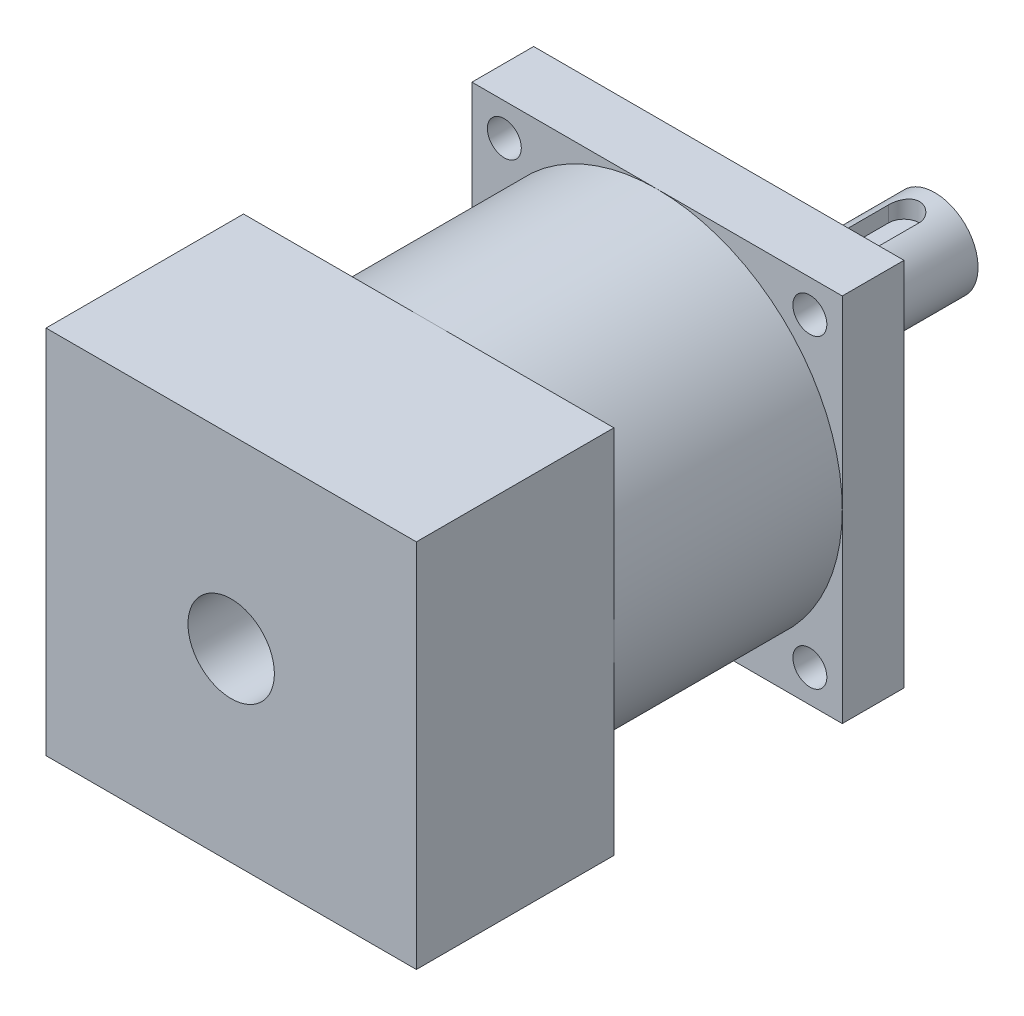
SolidWorks part; units mm, degrees
ref_plane "前视基准面" through (0, 0, 0) normal (0, 0, 1) x (1, 0, 0)
ref_plane "上视基准面" through (0, 0, 0) normal (0, 1, 0) x (1, 0, 0)
ref_plane "右视基准面" through (0, 0, 0) normal (1, 0, 0) x (0, 0, -1)
sketch "草图1" plane through (0, 0, 0) normal (0, 0, 1) x (1, 0, 0)
  line L1 (0, 0) -> (60, 0)
  line L2 (0, 0) -> (0, -60)
  line L3 (0, -60) -> (60, -60)
  line L4 (60, 0) -> (60, -60)
  dimension "D1" = 60
  dimension "D2" = 60
extrude "拉伸1" add sketch "草图1" along normal blind 10
sketch "草图3" plane through (0, 0, 10) normal (0, 0, 1) x (1, 0, 0)
  circle A0 centre (30, -30) radius 30
  dimension "D1" = 60
extrude "拉伸2" add sketch "草图3" along normal blind 37
sketch "草图4" plane through (0, 0, 47) normal (0, 0, 1) x (1, 0, 0)
  line L1 (0, 0) -> (60, 0)
  line L2 (0, 0) -> (0, -60)
  line L3 (0, -60) -> (60, -60)
  line L4 (60, 0) -> (60, -60)
extrude "拉伸3" add sketch "草图4" along normal blind 32
sketch "草图5" plane through (0, 0, 0) normal (0, 0, -1) x (-1, 0, 0)
  circle A0 centre (-30, -30) radius 25
extrude "拉伸4" add sketch "草图5" along normal blind 3
sketch "草图6" plane through (0, 0, -3) normal (0, 0, -1) x (-1, 0, 0)
  circle A0 centre (-30, -30) radius 8.5
extrude "拉伸5" add sketch "草图6" along normal blind 2
sketch "草图7" plane through (0, 0, -5) normal (0, 0, -1) x (-1, 0, 0)
  circle A0 centre (-30, -30) radius 7
extrude "拉伸6" add sketch "草图7" along normal blind 30
sketch "草图8" plane through (0, 0, 79) normal (0, 0, 1) x (1, 0, 0)
  circle A0 centre (30, -30) radius 7
extrude "切除-拉伸1" cut sketch "草图8" against normal blind 30
sketch "草图9" plane through (0, 0, 0) normal (0, 0, -1) x (-1, 0, 0)
  circle A1 centre (-5.2513, -5.2513) radius 2.75
  circle A2 centre (-5.2513, -54.7487) radius 2.75
  circle A3 centre (-54.7487, -54.7487) radius 2.75
  circle A4 centre (-54.7487, -5.2513) radius 2.75
extrude "切除-拉伸2" cut sketch "草图9" against normal blind 30
ref_plane "基准面2" through (0, -23, 0) normal (0, 1, 0) x (-1, 0, 0)
sketch "草图10" plane through (0, -23, 0) normal (0, 1, 0) x (-1, 0, 0)
  line L0 (-32.5, -10) -> (-32.5, -30)
  line L1 (-27.5, -10) -> (-27.5, -30)
  line L3 (-37, -35) -> (-23, -35) construction
  arc A0 (-32.5, -30) -> (-27.5, -30) centre (-30, -30) ccw
  arc A1 (-27.5, -10) -> (-32.5, -10) centre (-30, -10) ccw
  dimension "D1" = 5
  dimension "D2" = 5
  dimension "D4" = 5
extrude "切除-拉伸3" cut sketch "草图10" against normal blind 3
